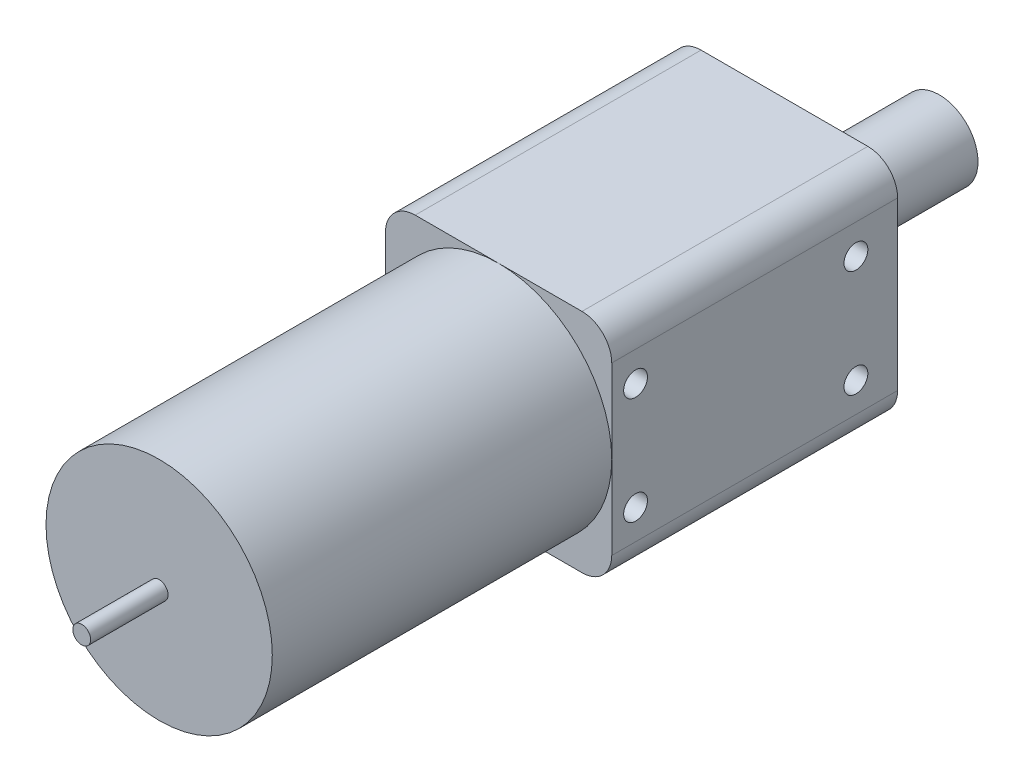
SolidWorks part; units mm, degrees
ref_plane "Front Plane" through (0, 0, 0) normal (0, 0, 1) x (1, 0, 0)
ref_plane "Top Plane" through (0, 0, 0) normal (0, 1, 0) x (1, 0, 0)
ref_plane "Right Plane" through (0, 0, 0) normal (1, 0, 0) x (0, 0, -1)
sketch "Sketch1" plane through (0, 0, 0) normal (0, 0, 1) x (1, 0, 0)
  circle A0 centre (0, 0) radius 19
extrude "Boss-Extrude1" add sketch "Sketch1" along normal blind 57
sketch "Sketch3" plane through (0, 0, 0) normal (0, 0, -1) x (-1, 0, 0)
  line L1 (-19, 19) -> (19, 19)
  line L2 (-19, 19) -> (-19, -19)
  line L3 (-19, -19) -> (19, -19)
  line L4 (19, 19) -> (19, -19)
  line L5 (-19, 19) -> (19, -19) construction
  line L6 (-19, -19) -> (19, 19) construction
  point P0 (0, 0)
extrude "Boss-Extrude3" add sketch "Sketch3" along normal blind 48
sketch "Sketch4" plane through (0, 0, -48) normal (0, 0, -1) x (-1, 0, 0)
  circle A0 centre (0, 0) radius 6.5
extrude "Boss-Extrude4" add sketch "Sketch4" along normal blind 26
sketch "Sketch5" plane through (0, 0, 57) normal (0, 0, 1) x (1, 0, 0)
  circle A0 centre (0, 0) radius 1.5
extrude "Boss-Extrude5" add sketch "Sketch5" along normal blind 13
fillet "Fillet1" radius 5 4 edges at (-19, 19, -24) (19, -19, -24) (19, 19, -24) (-19, -19, -24)
sketch "Sketch6" plane through (-19, 0, 0) normal (-1, 0, 0) x (0, 0, 1)
  line L0 (-48, 19) -> (0, 19) construction
  line L1 (0, 0) -> (0, 14) construction
  line L2 (0, -19) -> (-48, -19) construction
  line L3 (-48, -14) -> (-48, 14) construction
  circle A0 centre (-4, 9) radius 2
  circle A1 centre (-4, -9) radius 2
  circle A2 centre (-41, -9) radius 2
  circle A3 centre (-41, 9) radius 2
  dimension "D1" = 10
  dimension "D3" = 10
  dimension "D4" = 7
  dimension "D2" = 4
extrude "Cut-Extrude1" cut sketch "Sketch6" against normal blind 10
sketch "Sketch7" plane through (19, 0, 0) normal (1, 0, 0) x (0, 0, -1)
  line L0 (48, 14) -> (48, -14) construction
  line L1 (0, 19) -> (48, 19) construction
  line L2 (0, 0) -> (0, -14) construction
  line L3 (48, -19) -> (0, -19) construction
  line L4 (0, 14) -> (0, 0) construction
  circle A0 centre (41, 9) radius 2
  circle A1 centre (41, -9) radius 2
  circle A2 centre (4, -9) radius 2
  circle A3 centre (4, 9) radius 2
  dimension "D1" = 7
  dimension "D2" = 7
  dimension "D3" = 10
  dimension "D4" = 4
  dimension "D5" = 10
  dimension "D6" = 4
  dimension "D7" = 10
  dimension "D8" = 10
extrude "Cut-Extrude2" cut sketch "Sketch7" against normal blind 10
